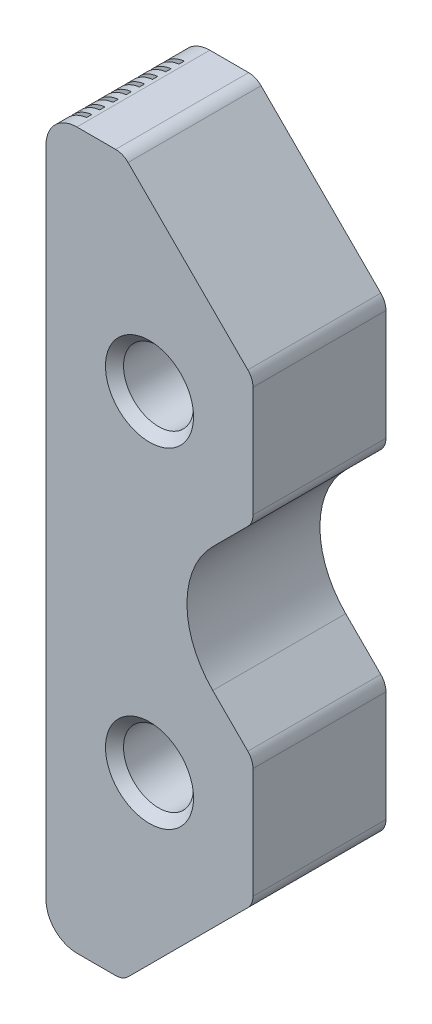
SolidWorks part; units mm, degrees
ref_plane "Front Plane" through (0, 0, 0) normal (0, 0, 1) x (1, 0, 0)
ref_plane "Top Plane" through (0, 0, 0) normal (0, 1, 0) x (1, 0, 0)
ref_plane "Right Plane" through (0, 0, 0) normal (1, 0, 0) x (0, 0, -1)
sketch "Sketch1" plane through (0, 0, 0) normal (0, 0, 1) x (1, 0, 0)
  line L0 (65.9035, 0) -> (74.7951, 0) construction
  line L1 (52.1716, 20.6375) -> (54.4091, 20.6375)
  line L2 (50.3936, 18.8595) -> (50.3936, -18.8595)
  line L3 (62.034, -13.4334) -> (55.1275, -20.3399)
  line L4 (62.3316, 12.715) -> (62.3316, 6.335)
  line L5 (60.0095, 3.5921) -> (62.034, 5.6166)
  line L6 (62.034, 13.4334) -> (55.1275, 20.3399)
  line L7 (60.0095, -3.5921) -> (62.034, -5.6166)
  line L8 (62.3316, -12.715) -> (62.3316, -6.335)
  line L9 (52.1716, -20.6375) -> (54.4091, -20.6375)
  circle A0 centre (56.3626, 9.525) radius 1.27 construction
  arc A1 (62.034, 5.6166) -> (62.3316, 6.335) centre (61.3156, 6.335) ccw
  circle A2 centre (56.3626, -9.525) radius 1.27 construction
  arc A3 (52.1716, 20.6375) -> (50.3936, 18.8595) centre (52.1716, 18.8595) ccw
  arc A4 (60.0095, 3.5921) -> (60.0095, -3.5921) centre (63.6016, 0) ccw
  arc A5 (62.3316, 12.715) -> (62.034, 13.4334) centre (61.3156, 12.715) ccw
  arc A6 (54.4091, 20.6375) -> (55.1275, 20.3399) centre (54.4091, 19.6215) cw
  arc A7 (54.4091, -20.6375) -> (55.1275, -20.3399) centre (54.4091, -19.6215) ccw
  arc A8 (62.3316, -12.715) -> (62.034, -13.4334) centre (61.3156, -12.715) cw
  arc A9 (52.1716, -20.6375) -> (50.3936, -18.8595) centre (52.1716, -18.8595) cw
  arc A10 (62.034, -5.6166) -> (62.3316, -6.335) centre (61.3156, -6.335) cw
  point P4 (56.3626, 0)
  point P15 (50.3936, 0)
  point P26 (62.3316, 9.525)
  point P37 (62.3316, -9.525)
  dimension "D4" = 2.54
  dimension "D6" = 5.969
  dimension "D7" = 1.778
  dimension "D8" = 5.08
  dimension "D9" = 1.016
  dimension "D2" = 11.938
  dimension "D3" = 56.3626
  dimension "D5" = 5.969
  dimension "D10" = 9.525
  dimension "D11" = 3.81
  dimension "D12" = 45
  dimension "D13" = 41.275
extrude "Boss-Extrude1" add sketch "Sketch1" against normal blind 7.6708
sketch "Sketch2" plane through (0, 0, 0) normal (0, 1, 0) x (1, 0, 0)
  line L1 (46.8884, 1.0668) -> (51.9684, 1.0668)
  line L2 (46.8884, 1.0668) -> (46.8884, 0.762)
  line L3 (46.8884, 0.762) -> (51.9684, 0.762)
  line L4 (51.9684, 1.0668) -> (51.9684, 0.762)
  dimension "D1" = 0.3048
  dimension "D2" = 1.5748
  dimension "D3" = 5.08
  dimension "D4" = 0.762
extrude "Cut-Extrude1" cut sketch "Sketch2" against normal mid plane 76.2
pattern_linear "LPattern1" count 8 spacing 0.762 along (0, 0, -1) of "Cut-Extrude1"
hole_wizard "#10-32 Tapped Hole1" positions "Sketch4" profile "Sketch3" tap size "#10-32" standard "Ansi Inch" end condition up to next
sketch "Sketch4" plane through (0, 0, 0) normal (0, 0, 1) x (1, 0, 0)
  point P0 (56.3626, 9.525)
  point P1 (56.3626, -9.525)
  dimension "D1" = 56.3626
  dimension "D2" = 9.525
  dimension "D3" = 9.525
sketch "Sketch3" plane through (56.3626, 9.525, 0) normal (1, 0, 0) x (0, -1, 0)
  line L0 (0, 0) -> (0, 7.6708)
  line L1 (0, 7.6708) -> (2.54, 7.6708)
  line L2 (2.0193, 7.1501) -> (2.0193, 0.5207)
  line L3 (2.0193, 0.5207) -> (2.54, 0)
  line L5 (2.54, 0) -> (0, 0)
  line L6 (-2.0193, 0.5207) -> (-2.54, 0) construction
  line L7 (2.54, 7.6708) -> (2.0193, 7.1501)
  line L8 (-2.54, 7.6708) -> (-2.0193, 7.1501) construction
  line L11 (0, -6.35) -> (0, 107.95) construction
  dimension "Thread Major Dia." = 4.0386
  dimension "Thru Tap Drill Depth" = 7.6708
  dimension "Near C'Sink Dia." = 5.08
  dimension "Near C'Sink Angle" = 90
  dimension "Far C'Sink Dia." = 5.08
  dimension "Far C'Sink Angle" = 90
